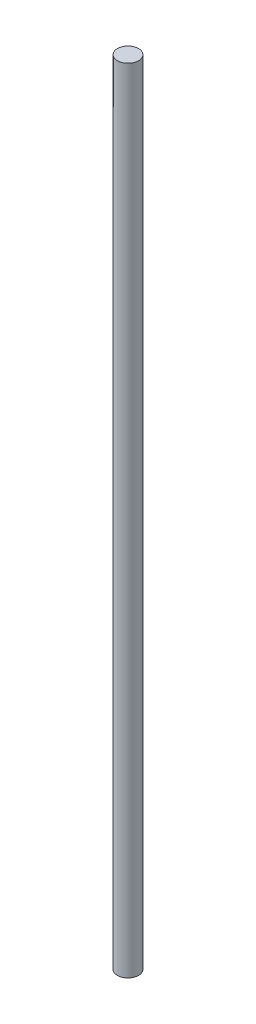
SolidWorks part; units mm, degrees
ref_plane "前视基准面" through (0, 0, 0) normal (0, 0, 1) x (1, 0, 0)
ref_plane "上视基准面" through (0, 0, 0) normal (0, 1, 0) x (1, 0, 0)
ref_plane "右视基准面" through (0, 0, 0) normal (1, 0, 0) x (0, 0, -1)
sketch "草图1" plane through (0, 0, 0) normal (0, 1, 0) x (1, 0, 0)
  circle A0 centre (0, 0) radius 1.5
  dimension "D1" = 3
extrude "凸台-拉伸1" add sketch "草图1" along normal blind 112.44
